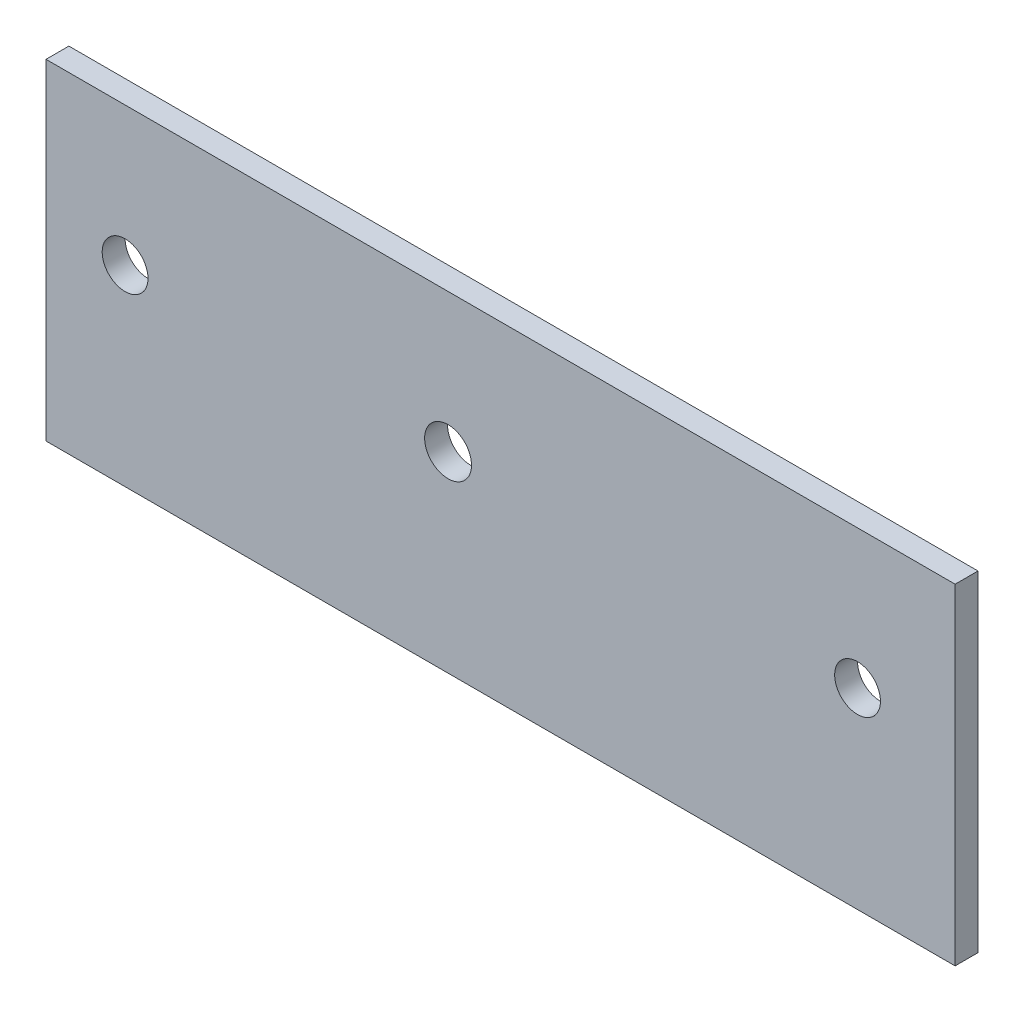
SolidWorks part; units mm, degrees
ref_plane "Front Plane" through (0, 0, 0) normal (0, 0, 1) x (1, 0, 0)
ref_plane "Top Plane" through (0, 0, 0) normal (0, 1, 0) x (1, 0, 0)
ref_plane "Right Plane" through (0, 0, 0) normal (1, 0, 0) x (0, 0, -1)
sketch "Sketch1" plane through (0, 0, 0) normal (0, 0, 1) x (1, 0, 0)
  line L1 (-36.3708, 19.2466) -> (89.7343, 19.2466)
  line L2 (-36.3708, 19.2466) -> (-36.3708, -26.6095)
  line L3 (-36.3708, -26.6095) -> (89.7343, -26.6095)
  line L4 (89.7343, 19.2466) -> (89.7343, -26.6095)
  circle A0 centre (19.3993, 0) radius 3.2512
  circle A1 centre (19.3993, 0) radius 3.175 construction
  circle A2 centre (76.2, 0) radius 3.175
  circle A3 centre (-25.4, 0) radius 3.175
  point P14 (-25.4, 0)
  dimension "D1" = 6.5024
  dimension "D2" = 6.35
  dimension "D3" = 6.35
extrude "Boss-Extrude1" add sketch "Sketch1" along normal blind 3.175
